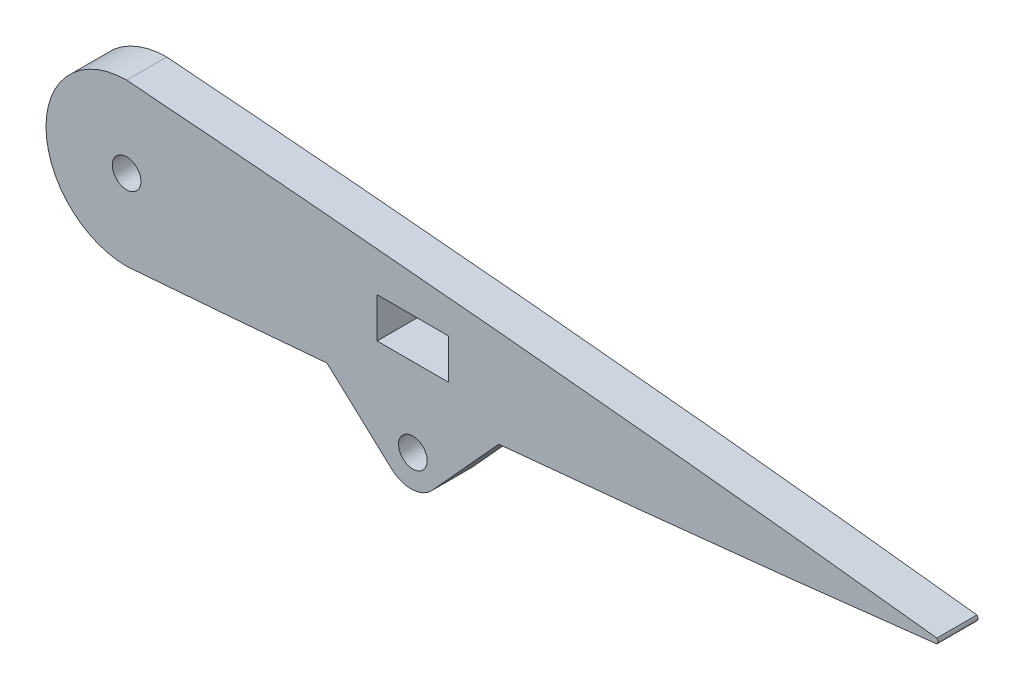
SolidWorks part; units mm, degrees
material "Фанера"
ref_plane "Front Plane" through (0, 0, 0) normal (0, 0, 1) x (1, 0, 0)
ref_plane "Top Plane" through (0, 0, 0) normal (0, 1, 0) x (1, 0, 0)
ref_plane "Right Plane" through (0, 0, 0) normal (1, 0, 0) x (0, 0, -1)
curve "Кривая1"
  spline degree 3 poles (110, 0, 0) (110.0276, -0.2367, 0) (110.0855, -0.7342, 0) (110.5302, -1.4271, 0) (111.1963, -2.0786, 0) (112.1098, -2.7013, 0) (113.2568, -3.2993, 0) (114.6379, -3.8731, 0) (116.2477, -4.4214, 0) (118.0813, -4.9426, 0) (120.1331, -5.4348, 0) (122.3972, -5.8961, 0) (124.8672, -6.3247, 0) (127.537, -6.7187, 0) (130.3997, -7.0764, 0) (133.4488, -7.3965, 0) (136.6771, -7.6776, 0) (140.0777, -7.9187, 0) (143.6433, -8.119, 0) (147.3662, -8.278, 0) (151.2389, -8.3955, 0) (155.2534, -8.4715, 0) (159.4016, -8.5065, 0) (163.6751, -8.501, 0) (168.0653, -8.456, 0) (172.5632, -8.3725, 0) (177.1595, -8.252, 0) (181.8446, -8.096, 0) (186.6087, -7.9062, 0) (191.4413, -7.6846, 0) (196.3316, -7.4331, 0) (201.2684, -7.1538, 0) (206.2396, -6.8489, 0) (211.233, -6.5205, 0) (216.2352, -6.1709, 0) (221.2323, -5.8022, 0) (226.2093, -5.417, 0) (231.1504, -5.0174, 0) (236.0382, -4.6058, 0) (240.8542, -4.1849, 0) (245.5777, -3.7574, 0) (250.1862, -3.3262, 0) (254.6542, -2.8948, 0) (258.9526, -2.4672, 0) (263.0477, -2.0479, 0) (266.899, -1.6426, 0) (270.4558, -1.2586, 0) (273.6512, -0.9053, 0) (276.3854, -0.5964, 0) (278.4526, -0.359, 0) (279.592, -0.2261, 0) (280, -0.1785, 0) knots 0 0 0 0 0.004099 0.008615 0.013935 0.020278 0.027753 0.03641 0.046266 0.05732 0.069559 0.082963 0.097507 0.113164 0.129903 0.14769 0.166492 0.186272 0.206992 0.228612 0.251092 0.274389 0.298458 0.323254 0.348728 0.37483 0.401509 0.42871 0.456376 0.484448 0.512864 0.541558 0.570462 0.599504 0.628607 0.65769 0.686667 0.715445 0.743924 0.771995 0.79954 0.826428 0.852512 0.877624 0.901571 0.924121 0.944989 0.963804 0.980044 0.992855 1 1 1 1
curve "Кривая2"
  spline degree 3 poles (280, 0.1785, 0) (279.592, 0.2261, 0) (278.4526, 0.359, 0) (276.3854, 0.5964, 0) (273.6512, 0.9053, 0) (270.4558, 1.2586, 0) (266.899, 1.6426, 0) (263.0477, 2.0479, 0) (258.9526, 2.4672, 0) (254.6542, 2.8948, 0) (250.1862, 3.3262, 0) (245.5777, 3.7574, 0) (240.8542, 4.1849, 0) (236.0382, 4.6058, 0) (231.1504, 5.0174, 0) (226.2093, 5.417, 0) (221.2323, 5.8022, 0) (216.2352, 6.1709, 0) (211.233, 6.5205, 0) (206.2396, 6.8489, 0) (201.2684, 7.1538, 0) (196.3316, 7.4331, 0) (191.4413, 7.6846, 0) (186.6087, 7.9062, 0) (181.8446, 8.096, 0) (177.1595, 8.252, 0) (172.5632, 8.3725, 0) (168.0653, 8.456, 0) (163.6751, 8.501, 0) (159.4016, 8.5065, 0) (155.2534, 8.4715, 0) (151.2389, 8.3955, 0) (147.3662, 8.278, 0) (143.6433, 8.119, 0) (140.0777, 7.9187, 0) (136.6771, 7.6776, 0) (133.4488, 7.3965, 0) (130.3997, 7.0764, 0) (127.537, 6.7187, 0) (124.8672, 6.3247, 0) (122.3972, 5.8961, 0) (120.1331, 5.4348, 0) (118.0813, 4.9426, 0) (116.2477, 4.4214, 0) (114.6379, 3.8731, 0) (113.2568, 3.2993, 0) (112.1098, 2.7013, 0) (111.1963, 2.0786, 0) (110.5302, 1.4271, 0) (110.0855, 0.7342, 0) (110.0276, 0.2367, 0) (110, 0, 0) knots 0 0 0 0 0.007145 0.019956 0.036196 0.055011 0.075879 0.098429 0.122376 0.147488 0.173572 0.20046 0.228005 0.256076 0.284555 0.313333 0.34231 0.371393 0.400496 0.429538 0.458442 0.487136 0.515552 0.543624 0.57129 0.598491 0.62517 0.651272 0.676746 0.701542 0.725611 0.748908 0.771388 0.793008 0.813728 0.833508 0.85231 0.870097 0.886836 0.902493 0.917037 0.930441 0.94268 0.953734 0.96359 0.972247 0.979722 0.986065 0.991385 0.995901 1 1 1 1
sketch "Эскиз1" plane through (0, 0, 0) normal (0, 0, 1) x (1, 0, 0)
  line L0 (105.1708, 0) -> (280.7263, 0) construction
  line L1 (280.0739, 0) -> (280.0739, 24.3846) construction
  line L2 (110, -5.3315) -> (110, 17.5304) construction
  line L3 (152.5185, 18.8331) -> (152.5185, -21.3473) construction
  line L4 (223.3826, 13.2402) -> (223.3826, -18.4275) construction
  line L5 (217.7476, 6.0581) -> (217.7476, -6.0581)
  line L6 (127.0185, -3) -> (140.0185, -3)
  line L7 (125.0185, -1) -> (125.0185, 1)
  line L8 (127.0185, 3) -> (140.0185, 3)
  line L9 (142.0185, -1) -> (142.0185, 1)
  line L10 (125.0185, -3) -> (142.0185, 3) construction
  line L11 (125.0185, 3) -> (142.0185, -3) construction
  line L12 (165.0185, -4.5) -> (185.0185, -4.5)
  line L13 (163.0185, -2.5) -> (163.0185, 2.5)
  line L14 (165.0185, 4.5) -> (185.0185, 4.5)
  line L15 (187.0185, -2.5) -> (187.0185, 2.5)
  line L16 (163.0185, -4.5) -> (187.0185, 4.5) construction
  line L17 (163.0185, 4.5) -> (187.0185, -4.5) construction
  line L18 (243.3826, 16.1127) -> (243.3826, -19.2013) construction
  line L19 (240.8826, -1.4) -> (245.8826, -1.4)
  line L20 (240.8826, -1.4) -> (240.8826, 1.4)
  line L21 (240.8826, 1.4) -> (245.8826, 1.4)
  line L22 (245.8826, -1.4) -> (245.8826, 1.4)
  line L23 (240.8826, -1.4) -> (245.8826, 1.4) construction
  line L24 (240.8826, 1.4) -> (245.8826, -1.4) construction
  line L25 (237.3826, -4.4873) -> (241.9021, -8.6397)
  line L26 (244.7351, -8.5123) -> (249.3826, -3.4001)
  arc A0 (280, 0.1785) -> (280, -0.1785) centre (279.8215, 0) cw
  circle A1 centre (152.5185, 0) radius 4
  circle A2 centre (197.5185, 0) radius 4
  arc A3 (185.0185, 4.5) -> (187.0185, 2.5) centre (185.0185, 2.5) cw
  arc A4 (185.0185, -4.5) -> (187.0185, -2.5) centre (185.0185, -2.5) ccw
  arc A5 (165.0185, -4.5) -> (163.0185, -2.5) centre (165.0185, -2.5) cw
  arc A6 (163.0185, 2.5) -> (165.0185, 4.5) centre (165.0185, 2.5) cw
  arc A7 (125.0185, 1) -> (127.0185, 3) centre (127.0185, 1) cw
  arc A8 (127.0185, -3) -> (125.0185, -1) centre (127.0185, -1) cw
  arc A9 (140.0185, -3) -> (142.0185, -1) centre (140.0185, -1) ccw
  arc A10 (140.0185, 3) -> (142.0185, 1) centre (140.0185, 1) cw
  arc A11 (223.3826, 5.635) -> (223.3826, -5.635) centre (223.3826, 0) ccw
  circle A12 centre (223.3826, 0) radius 1
  circle A13 centre (243.3826, -6.9031) radius 1
  arc A14 (241.9021, -8.6397) -> (244.7351, -8.5123) centre (243.2552, -7.1669) ccw
  spline S0 degree 3 poles (110, 0) (110.0276, -0.2367) (110.0855, -0.7342) (110.5302, -1.4271) (111.1963, -2.0786) (112.1098, -2.7013) (113.2568, -3.2993) (114.6379, -3.8731) (116.2477, -4.4214) (118.0813, -4.9426) (120.1331, -5.4348) (122.3972, -5.8961) (124.8672, -6.3247) (127.537, -6.7187) (130.3997, -7.0764) (133.4488, -7.3965) (136.6771, -7.6776) (140.0777, -7.9187) (143.6433, -8.119) (147.3662, -8.278) (151.2389, -8.3955) (155.2534, -8.4715) (159.4016, -8.5065) (163.6751, -8.501) (168.0653, -8.456) (172.5632, -8.3725) (177.1595, -8.252) (181.8446, -8.096) (186.6087, -7.9062) (191.4413, -7.6846) (196.3316, -7.4331) (201.2684, -7.1538) (206.2396, -6.8489) (211.233, -6.5205) (216.2352, -6.1709) (221.2323, -5.8022) (226.2093, -5.417) (231.1504, -5.0174) (236.0382, -4.6058) (240.8542, -4.1849) (247.0711, -3.6222) (253.1161, -3.0479) (258.9526, -2.4672) (263.0477, -2.0479) (266.899, -1.6426) (270.4558, -1.2586) (273.6512, -0.9053) (276.3854, -0.5964) (278.4526, -0.359) (279.592, -0.2261) (280, -0.1785) knots 0 0 0 0 0.004099 0.008615 0.013935 0.020278 0.027753 0.03641 0.046266 0.05732 0.069559 0.082963 0.097507 0.113164 0.129903 0.14769 0.166492 0.186272 0.206992 0.228612 0.251092 0.274389 0.298458 0.323254 0.348728 0.37483 0.401509 0.42871 0.456376 0.484448 0.512864 0.541558 0.570462 0.599504 0.628607 0.65769 0.686667 0.715445 0.743924 0.771995 0.79954 0.852512 0.877624 0.901571 0.924121 0.944989 0.963804 0.980044 0.992855 1 1 1 1 construction
  spline S1 degree 3 poles (751.5383, 1938.3796) (440.561, -28.5775) (359.5279, -8.955) (276.3854, 0.5964) (273.6512, 0.9053) (270.4558, 1.2586) (266.899, 1.6426) (263.0477, 2.0479) (258.9526, 2.4672) (253.1161, 3.0479) (247.0711, 3.6222) (240.8542, 4.1849) (236.0382, 4.6058) (231.1504, 5.0174) (226.2093, 5.417) (221.2323, 5.8022) (216.2352, 6.1709) (211.233, 6.5205) (206.2396, 6.8489) (201.2684, 7.1538) (196.3316, 7.4331) (191.4413, 7.6846) (186.6087, 7.9062) (181.8446, 8.096) (177.1595, 8.252) (172.5632, 8.3725) (168.0653, 8.456) (163.6751, 8.501) (159.4016, 8.5065) (155.2534, 8.4715) (151.2389, 8.3955) (147.3662, 8.278) (143.6433, 8.119) (140.0777, 7.9187) (136.6771, 7.6776) (133.4488, 7.3965) (130.3997, 7.0764) (127.537, 6.7187) (124.8672, 6.3247) (122.3972, 5.8961) (120.1331, 5.4348) (118.0813, 4.9426) (116.2477, 4.4214) (114.6379, 3.8731) (113.2568, 3.2993) (112.1098, 2.7013) (111.1963, 2.0786) (110.5302, 1.4271) (105.6546, -6.1694) (164.5198, -33.7739) (-1801.974, 584.7691) knots -1.419625 -1.419625 -1.419625 -1.419625 0.007145 0.019956 0.036196 0.055011 0.075879 0.098429 0.122376 0.147488 0.20046 0.228005 0.256076 0.284555 0.313333 0.34231 0.371393 0.400496 0.429538 0.458442 0.487136 0.515552 0.543624 0.57129 0.598491 0.62517 0.651272 0.676746 0.701542 0.725611 0.748908 0.771388 0.793008 0.813728 0.833508 0.85231 0.870097 0.886836 0.902493 0.917037 0.930441 0.94268 0.953734 0.96359 0.972247 0.979722 0.986065 0.991385 0.995901 1.138851 1.138851 1.138851 1.138851 only from (280, 0.1785) to (110, 0) construction
  spline S2 degree 3 poles (110, 0) (110.0276, -0.2367) (110.0855, -0.7342) (110.5302, -1.4271) (111.1963, -2.0786) (112.1098, -2.7013) (113.2568, -3.2993) (114.6379, -3.8731) (116.2477, -4.4214) (118.0813, -4.9426) (120.1331, -5.4348) (122.3972, -5.8961) (124.8672, -6.3247) (127.537, -6.7187) (130.3997, -7.0764) (133.4488, -7.3965) (136.6771, -7.6776) (140.0777, -7.9187) (143.6433, -8.119) (147.3662, -8.278) (151.2389, -8.3955) (155.2534, -8.4715) (159.4016, -8.5065) (163.6751, -8.501) (168.0653, -8.456) (172.5632, -8.3725) (177.1595, -8.252) (181.8446, -8.096) (186.6087, -7.9062) (191.4413, -7.6846) (196.3316, -7.4331) (201.2684, -7.1538) (206.2396, -6.8489) (211.233, -6.5205) (216.2352, -6.1709) (221.2323, -5.8022) (226.2093, -5.417) (231.1504, -5.0174) (234.8707, -4.7041) (236.9422, -4.5255) (237.3826, -4.4873) knots 0 0 0 0 0.004099 0.008615 0.013935 0.020278 0.027753 0.03641 0.046266 0.05732 0.069559 0.082963 0.097507 0.113164 0.129903 0.14769 0.166492 0.186272 0.206992 0.228612 0.251092 0.274389 0.298458 0.323254 0.348728 0.37483 0.401509 0.42871 0.456376 0.484448 0.512864 0.541558 0.570462 0.599504 0.628607 0.65769 0.686667 0.715445 0.743924 0.751613 0.751613 0.751613 0.751613
  spline S3 degree 3 poles (280, 0.1785) (279.592, 0.2261) (278.4526, 0.359) (276.3854, 0.5964) (273.6512, 0.9053) (270.4558, 1.2586) (266.899, 1.6426) (263.0477, 2.0479) (258.9526, 2.4672) (253.1161, 3.0479) (247.0711, 3.6222) (240.8542, 4.1849) (236.0382, 4.6058) (231.1504, 5.0174) (226.2093, 5.417) (221.2323, 5.8022) (216.2352, 6.1709) (211.233, 6.5205) (206.2396, 6.8489) (201.2684, 7.1538) (196.3316, 7.4331) (191.4413, 7.6846) (186.6087, 7.9062) (181.8446, 8.096) (177.1595, 8.252) (172.5632, 8.3725) (168.0653, 8.456) (163.6751, 8.501) (159.4016, 8.5065) (155.2534, 8.4715) (151.2389, 8.3955) (147.3662, 8.278) (143.6433, 8.119) (140.0777, 7.9187) (136.6771, 7.6776) (133.4488, 7.3965) (130.3997, 7.0764) (127.537, 6.7187) (124.8672, 6.3247) (122.3972, 5.8961) (120.1331, 5.4348) (118.0813, 4.9426) (116.2477, 4.4214) (114.6379, 3.8731) (113.2568, 3.2993) (112.1098, 2.7013) (111.1963, 2.0786) (110.5302, 1.4271) (110.0855, 0.7342) (110.0276, 0.2367) (110, 0) knots 0 0 0 0 0.007145 0.019956 0.036196 0.055011 0.075879 0.098429 0.122376 0.147488 0.20046 0.228005 0.256076 0.284555 0.313333 0.34231 0.371393 0.400496 0.429538 0.458442 0.487136 0.515552 0.543624 0.57129 0.598491 0.62517 0.651272 0.676746 0.701542 0.725611 0.748908 0.771388 0.793008 0.813728 0.833508 0.85231 0.870097 0.886836 0.902493 0.917037 0.930441 0.94268 0.953734 0.96359 0.972247 0.979722 0.986065 0.991385 0.995901 1 1 1 1
  spline S4 degree 3 poles (249.3826, -3.4001) (251.1586, -3.2323) (254.3712, -2.923) (258.9526, -2.4672) (263.0477, -2.0479) (266.899, -1.6426) (270.4558, -1.2586) (273.6512, -0.9053) (276.3854, -0.5964) (278.4526, -0.359) (279.592, -0.2261) (280, -0.1785) knots 0.821481 0.821481 0.821481 0.821481 0.852512 0.877624 0.901571 0.924121 0.944989 0.963804 0.980044 0.992855 1 1 1 1
  point P19 (175.0185, 0)
  point P22 (133.5185, 0)
  point P31 (223.3826, -5.635)
  point P54 (223.3826, 5.635)
  point P55 (223.3826, -5.635)
  point P56 (223.3826, 5.635)
  point P63 (243.3826, 0)
  point P77 (243.3826, -10)
  dimension "D1" = 0.2524
  dimension "D3" = 8
  dimension "D13" = 2
  dimension "D14" = 5.635
  dimension "D15" = 2
  dimension "D22" = 2
  dimension "D23" = 2
  dimension "D2" = 170.0739
  dimension "D4" = 42.5185
  dimension "D5" = 56.6913
  dimension "D6" = 45
  dimension "D7" = 6
  dimension "D8" = 17
  dimension "D9" = 19
  dimension "D10" = 22.5
  dimension "D11" = 9
  dimension "D12" = 24
  dimension "D16" = 2.8
  dimension "D17" = 5
  dimension "D18" = 20
  dimension "D19" = 6
  dimension "D20" = 6
  dimension "D21" = 10
extrude "Бобышка-Вытянуть1" add sketch "Эскиз1" along normal mid plane 2.8 contours A0 S3 A11 S2 A12
equation "\"D4@Эскиз1\"=\"D2@Эскиз1\"/4"
equation "\"D5@Эскиз1\"=\"D2@Эскиз1\"/3"
equation "\"D10@Эскиз1\"=\"D6@Эскиз1\"/2"
